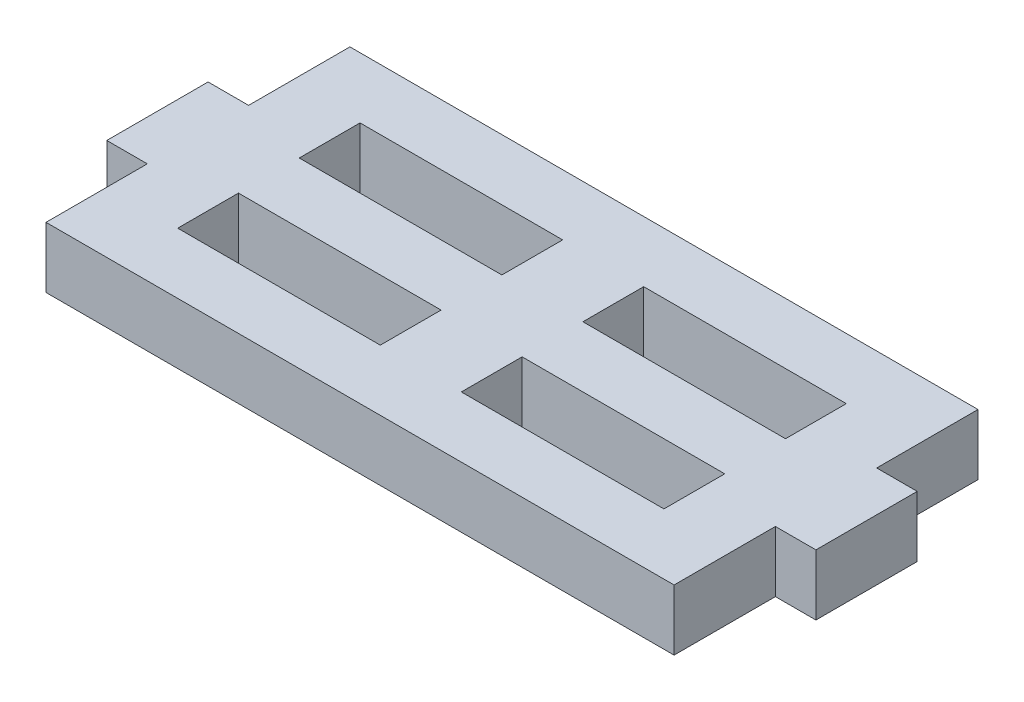
SolidWorks part; units mm, degrees
material "Acrylic (Medium-high impact)"
ref_plane "Front Plane" through (0, 0, 0) normal (0, 0, 1) x (1, 0, 0)
ref_plane "Top Plane" through (0, 0, 0) normal (0, 1, 0) x (1, 0, 0)
ref_plane "Right Plane" through (0, 0, 0) normal (1, 0, 0) x (0, 0, -1)
sketch "Sketch1" plane through (0, 0, 0) normal (0, 1, 0) x (1, 0, 0)
  line L1 (17.5, -7.5) -> (-17.5, -7.5)
  line L2 (17.5, -7.5) -> (17.5, 7.5)
  line L3 (17.5, 7.5) -> (-17.5, 7.5)
  line L4 (-17.5, -7.5) -> (-17.5, 7.5)
  line L5 (17.5, -7.5) -> (-17.5, 7.5) construction
  line L6 (17.5, 7.5) -> (-17.5, -7.5) construction
  point P0 (0, 0)
  dimension "D1" = 15
  dimension "D2" = 35
extrude "Boss-Extrude1" add sketch "Sketch1" along normal blind 3
sketch "Sketch2" plane through (0, 3, 0) normal (0, 1, 0) x (1, 0, 0)
  line L0 (-17.5, 0) -> (17.5, 0) construction
  line L1 (-17.5, 7.5) -> (-17.5, -7.5) construction
  line L2 (17.5, -7.5) -> (17.5, 7.5) construction
  line L3 (-12, -4.5) -> (-12, -1.5)
  line L4 (-12, 4.5) -> (-2, 4.5)
  line L5 (-12, 4.5) -> (-12, 1.5)
  line L6 (-12, 1.5) -> (-2, 1.5)
  line L7 (-2, 4.5) -> (-2, 1.5)
  line L8 (-12, 4.5) -> (-2, 1.5) construction
  line L9 (-12, 1.5) -> (-2, 4.5) construction
  line L10 (-12, -1.5) -> (-2, -1.5)
  line L11 (-2, -4.5) -> (-2, -1.5)
  line L12 (-12, -4.5) -> (-2, -4.5)
  line L13 (0, 7.5) -> (0, -7.5) construction
  line L14 (17.5, 7.5) -> (-17.5, 7.5) construction
  line L15 (-17.5, -7.5) -> (17.5, -7.5) construction
  line L16 (12, -4.5) -> (12, -1.5)
  line L17 (12, -4.5) -> (2, -4.5)
  line L18 (2, -4.5) -> (2, -1.5)
  line L19 (12, -1.5) -> (2, -1.5)
  line L20 (12, 4.5) -> (12, 1.5)
  line L21 (12, 1.5) -> (2, 1.5)
  line L22 (2, 4.5) -> (2, 1.5)
  line L23 (12, 4.5) -> (2, 4.5)
  point P6 (-7, 3)
  dimension "D1" = 10
  dimension "D2" = 3
  dimension "D3" = 3
  dimension "D4" = 7
extrude "Cut-Extrude1" cut sketch "Sketch2" against normal blind 3
sketch "Sketch3" plane through (0, 3, 0) normal (0, 1, 0) x (1, 0, 0)
  line L0 (17.5, 7.5) -> (-17.5, 7.5) construction
  line L1 (17.5, 2.5) -> (15.5, 2.5)
  line L2 (17.5, 2.5) -> (17.5, 7.5)
  line L3 (17.5, 7.5) -> (15.5, 7.5)
  line L4 (15.5, 2.5) -> (15.5, 7.5)
  line L5 (17.5, 2.5) -> (15.5, 7.5) construction
  line L6 (17.5, 7.5) -> (15.5, 2.5) construction
  line L7 (17.5, -7.5) -> (17.5, 7.5) construction
  line L8 (0, 7.5) -> (0, -7.3114) construction
  line L9 (-17.5, 0) -> (14.6895, 0) construction
  line L10 (-17.5, 7.5) -> (-17.5, -7.5) construction
  line L11 (17.5, -2.5) -> (15.5, -2.5)
  line L12 (17.5, -2.5) -> (17.5, -7.5)
  line L13 (17.5, -7.5) -> (15.5, -7.5)
  line L14 (15.5, -2.5) -> (15.5, -7.5)
  line L15 (-17.5, -7.5) -> (-15.5, -7.5)
  line L16 (-15.5, -2.5) -> (-15.5, -7.5)
  line L17 (-17.5, -2.5) -> (-15.5, -2.5)
  line L18 (-17.5, -2.5) -> (-17.5, -7.5)
  line L19 (-17.5, 2.5) -> (-15.5, 2.5)
  line L20 (-15.5, 2.5) -> (-15.5, 7.5)
  line L21 (-17.5, 2.5) -> (-17.5, 7.5)
  line L22 (-17.5, 7.5) -> (-15.5, 7.5)
  point P0 (16.5, 5)
  dimension "D1" = 5
  dimension "D2" = 2
  dimension "D3" = 1
extrude "Cut-Extrude2" cut sketch "Sketch3" against normal blind 3
